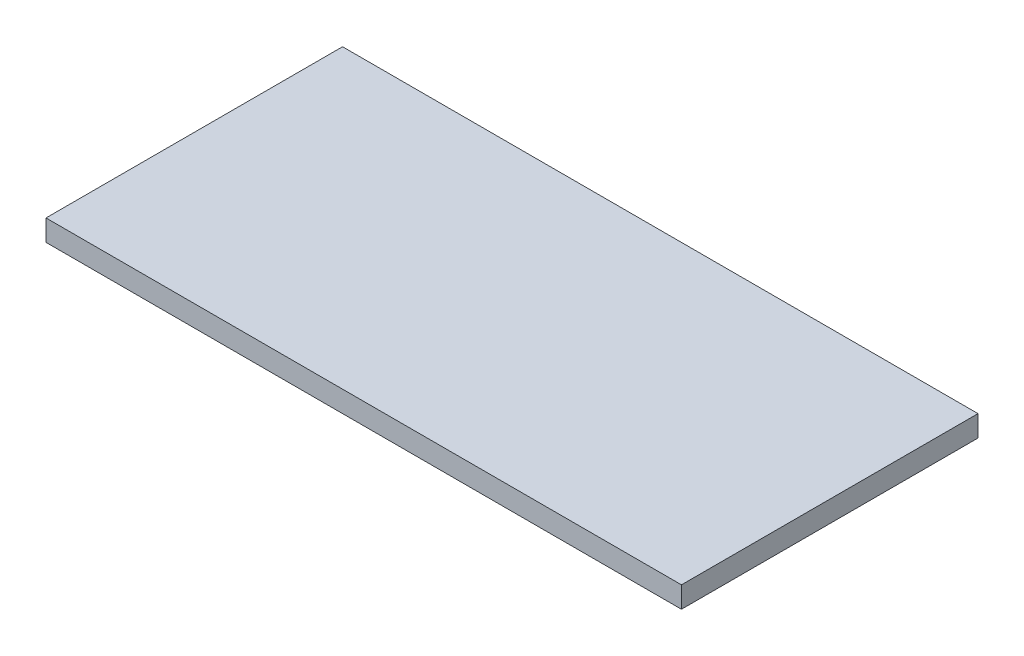
SolidWorks part; units mm, degrees
ref_plane "Front Plane" through (0, 0, 0) normal (0, 0, 1) x (1, 0, 0)
ref_plane "Top Plane" through (0, 0, 0) normal (0, 1, 0) x (1, 0, 0)
ref_plane "Right Plane" through (0, 0, 0) normal (1, 0, 0) x (0, 0, -1)
sketch "Sketch1" plane through (0, 0, 0) normal (0, 1, 0) x (1, 0, 0)
  line L1 (-77.3921, 30.0375) -> (72.6079, 30.0375)
  line L2 (-77.3921, 30.0375) -> (-77.3921, -39.9625)
  line L3 (-77.3921, -39.9625) -> (72.6079, -39.9625)
  line L4 (72.6079, 30.0375) -> (72.6079, -39.9625)
  dimension "D1" = 150
  dimension "D2" = 70
extrude "Boss-Extrude1" add sketch "Sketch1" along normal blind 5
